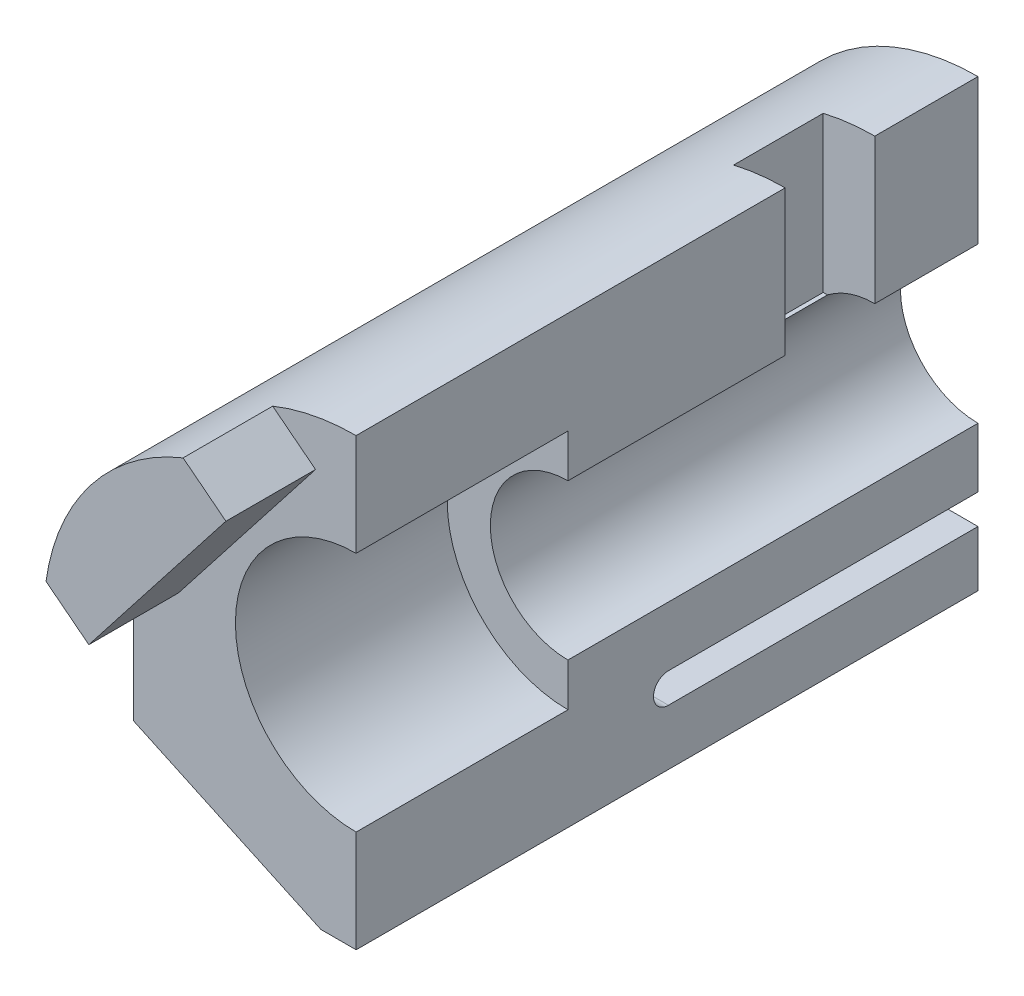
SolidWorks part; units mm, degrees
material "1060 Alloy"
ref_plane "Front Plane" through (0, 0, 0) normal (0, 0, 1) x (1, 0, 0)
ref_plane "Top Plane" through (0, 0, 0) normal (0, 1, 0) x (1, 0, 0)
ref_plane "Right Plane" through (0, 0, 0) normal (1, 0, 0) x (0, 0, -1)
sketch "Sketch1" plane through (0, 0, 0) normal (0, 0, 1) x (1, 0, 0)
  line L0 (0, 0) -> (-13, 0)
  line L1 (0, 53.425) -> (0, 0)
  line L2 (-82, 32.052) -> (-82, 82)
  line L3 (-13, 0) -> (-82, 32.052)
  line L4 (0, 110.575) -> (0, 164)
  arc A0 (0, 110.575) -> (0, 53.425) centre (0, 82) ccw
  arc A1 (0, 164) -> (-82, 82) centre (0, 82) ccw
  dimension "D4" = 57.15
  dimension "D5" = 164
  dimension "D1" = 13
  dimension "D2" = 82
  dimension "D3" = 82
extrude "Boss-Extrude1" add sketch "Sketch1" along normal blind 262
sketch "Sketch2" plane through (0, 0, 262) normal (0, 0, 1) x (1, 0, 0)
  line L0 (0, 53.425) -> (0, 0)
  line L1 (-13, 0) -> (0, 0) construction
  line L2 (-14.9464, 145.7072) -> (-65.4307, 81.0903)
  line L3 (-65.4307, 81.0903) -> (-81.202, 93.4122)
  line L4 (-14.9464, 145.7072) -> (-30.7177, 158.0291)
  line L6 (-82, 32.052) -> (-13, 0)
  line L7 (-13, 0) -> (0, 0)
  line L8 (0, 110.575) -> (0, 164)
  line L9 (-82, 32.052) -> (-82, 82)
  arc A1 (0, 164) -> (-82, 82) centre (0, 82) ccw construction
  arc A3 (0, 53.425) -> (0, 110.575) centre (0, 82) cw
  arc A4 (0, 110.575) -> (0, 53.425) centre (0, 82) ccw construction
  arc A5 (0, 164) -> (-30.7177, 158.0291) centre (0, 82) ccw
  arc A6 (-81.202, 93.4122) -> (-82, 82) centre (0, 82) ccw
  point P9 (-40.1885, 113.3987)
  dimension "D1" = 38
  dimension "D4" = 51
  dimension "D5" = 38
extrude "Cut-Extrude3" cut sketch "Sketch2" against normal blind 33
sketch "Sketch4" plane through (0, 0, 229) normal (0, 0, 1) x (1, 0, 0)
  circle A0 centre (0, 82) radius 44.45
  dimension "D1" = 88.9
extrude "Cut-Extrude4" cut sketch "Sketch4" against normal blind 78
sketch "Sketch6" plane through (0, 0, 0) normal (1, 0, 0) x (0, 0, -1)
  line L2 (-229, 164) -> (0, 164) construction
  line L3 (-71, 164) -> (-38, 164)
  line L6 (-71, 164) -> (-71, 104.6507)
  line L7 (-71, 104.6507) -> (-38, 104.6507)
  line L8 (-38, 104.6507) -> (-38, 164)
  dimension "D1" = 38
  dimension "D2" = 33
extrude "Cut-Extrude6" cut sketch "Sketch6" against normal blind 19
sketch "Sketch7" plane through (0, 0, 0) normal (1, 0, 0) x (0, 0, -1)
  line L6 (-229, 0) -> (0, 0) construction
  line L7 (-114, 20.5) -> (0, 20.5)
  line L8 (0, 0) -> (0, 53.425) construction
  line L9 (0, 20.5) -> (0, 31.5)
  line L10 (0, 31.5) -> (-114, 31.5)
  circle A1 centre (-114, 26) radius 5.5
  line M8 (0, 0) -> (0, 53.425)
  dimension "D1" = 11
  dimension "D2" = 26
  dimension "D3" = 114
extrude "Cut-Extrude7" cut sketch "Sketch7" against normal blind 13 contours A1 L7 L10 M8 | A1
